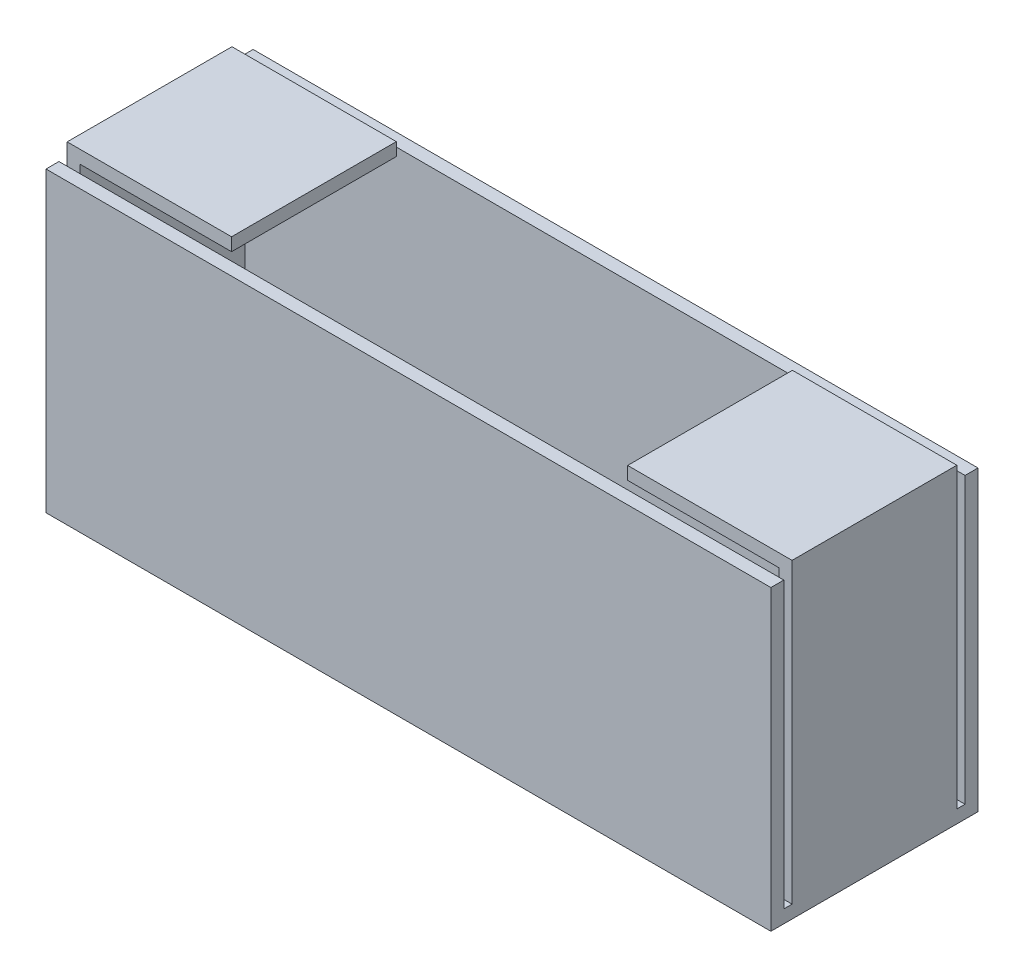
SolidWorks part; units mm, degrees
ref_plane "Front Plane" through (0, 0, 0) normal (0, 0, 1) x (1, 0, 0)
ref_plane "Top Plane" through (0, 0, 0) normal (0, 1, 0) x (1, 0, 0)
ref_plane "Right Plane" through (0, 0, 0) normal (1, 0, 0) x (0, 0, -1)
sketch "Sketch1" plane through (0, 0, 0) normal (0, 1, 0) x (1, 0, 0)
  line L1 (-28, -8) -> (28, -8)
  line L2 (-28, -8) -> (-28, 8)
  line L3 (-28, 8) -> (28, 8)
  line L4 (28, -8) -> (28, 8)
  line L5 (-28, -8) -> (28, 8) construction
  line L6 (-28, 8) -> (28, -8) construction
  point P0 (0, 0)
  dimension "D1" = 56
  dimension "D2" = 16
extrude "Boss-Extrude1" add sketch "Sketch1" along normal blind 1
sketch "Sketch2" plane through (0, 1, 0) normal (0, 1, 0) x (1, 0, 0)
  line L0 (27, 7) -> (28, 7)
  line L1 (-28, -8) -> (28, -8)
  line L2 (-28, -8) -> (-28, 8)
  line L3 (-28, 8) -> (28, 8)
  line L4 (28, -8) -> (28, 8)
  line L5 (-28, -8) -> (28, 8) construction
  line L6 (-28, 8) -> (28, -8) construction
  line L7 (-27, -7) -> (27, -7)
  line L8 (-27, -7) -> (-27, 7)
  line L9 (-27, 7) -> (27, 7)
  line L10 (27, -7) -> (27, 7)
  line L11 (-27, -7) -> (27, 7) construction
  line L12 (-27, 7) -> (27, -7) construction
  line L13 (27, -7) -> (28, -7)
  line L14 (-27, 7) -> (-28, 7)
  line L15 (-27, -7) -> (-28, -7)
  point P0 (0, 0)
  point P7 (0, 0)
  line M5 (28, -8) -> (28, 8)
  line M6 (28, 8) -> (-28, 8)
  line M7 (-28, 8) -> (-28, -8)
  line M8 (-28, -8) -> (28, -8)
  dimension "D1" = 1
  dimension "D2" = 1
extrude "Boss-Extrude2" add sketch "Sketch2" along normal blind 22 contours L7 L15 L13 M7 M8 M5 | L14 L9 L0 M5 M6 M7
sketch "Sketch3" plane through (0, 1, 0) normal (0, 1, 0) x (1, 0, 0)
  line L0 (28, -7) -> (28, 7) construction
  line L1 (28, 6.365) -> (27, 6.365)
  line L2 (28, 6.365) -> (28, -6.365)
  line L3 (28, -6.365) -> (27, -6.365)
  line L4 (27, 6.365) -> (27, -6.365)
  line L5 (28, 7) -> (-28, 7) construction
  line L6 (-28, -7) -> (28, -7) construction
  line L7 (0, 8) -> (0, -8) construction
  line L8 (28, 8) -> (-28, 8) construction
  line L9 (-28, -8) -> (28, -8) construction
  line L10 (-28, -6.365) -> (-27, -6.365)
  line L11 (-27, 6.365) -> (-27, -6.365)
  line L12 (-28, 6.365) -> (-27, 6.365)
  line L13 (-28, 6.365) -> (-28, -6.365)
  dimension "D1" = 1
  dimension "D2" = 0.635
  dimension "D3" = 0.635
extrude "Boss-Extrude3" add sketch "Sketch3" along normal blind 22
sketch "Sketch4" plane through (0, 23, 0) normal (0, 1, 0) x (1, 0, 0)
  line L0 (0, 8) -> (0, -8) construction
  line L1 (-28, -6.365) -> (-15.3, -6.365)
  line L2 (-28, -6.365) -> (-28, 6.365)
  line L3 (-28, 6.365) -> (-15.3, 6.365)
  line L4 (-15.3, -6.365) -> (-15.3, 6.365)
  line L5 (28, 8) -> (-28, 8) construction
  line L6 (-28, -8) -> (28, -8) construction
  line L7 (28, -6.365) -> (15.3, -6.365)
  line L8 (15.3, -6.365) -> (15.3, 6.365)
  line L9 (28, 6.365) -> (15.3, 6.365)
  line L10 (28, 6.365) -> (28, -6.365)
  dimension "D1" = 12.7
extrude "Boss-Extrude4" add sketch "Sketch4" along normal blind 1
